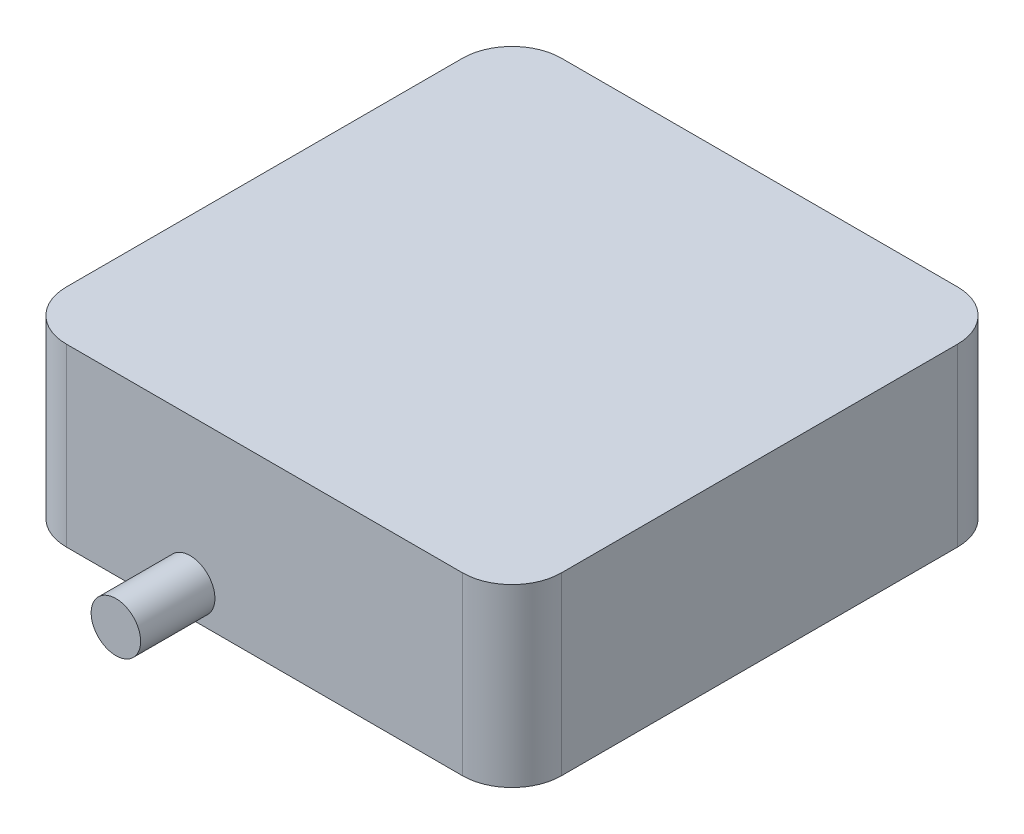
SolidWorks part; units mm, degrees
ref_plane "Front Plane" through (0, 0, 0) normal (0, 0, 1) x (1, 0, 0)
ref_plane "Top Plane" through (0, 0, 0) normal (0, 1, 0) x (1, 0, 0)
ref_plane "Right Plane" through (0, 0, 0) normal (1, 0, 0) x (0, 0, -1)
sketch "Sketch1" plane through (0, 0, 0) normal (0, 1, 0) x (1, 0, 0)
  line L1 (-100, -100) -> (100, -100)
  line L2 (-100, -100) -> (-100, 100)
  line L3 (-100, 100) -> (100, 100)
  line L4 (100, -100) -> (100, 100)
  line L5 (-100, -100) -> (100, 100) construction
  line L6 (-100, 100) -> (100, -100) construction
  point P0 (0, 0)
  dimension "D1" = 200
  dimension "D2" = 200
extrude "Boss-Extrude1" add sketch "Sketch1" along normal blind 71
fillet "Fillet1" radius 20 4 edges at (-100, 35.5, -100) (100, 35.5, -100) (100, 35.5, 100) (-100, 35.5, 100)
sketch "Sketch2" plane through (0, 0, 100) normal (0, 0, 1) x (1, 0, 0)
  line L0 (-30, 71) -> (-30, 0) construction
  line L1 (-80, 71) -> (80, 71) construction
  line L2 (-80, 0) -> (80, 0) construction
  line L3 (-100, 0) -> (-100, 71) construction
  line L4 (-100, 12) -> (100, 12) construction
  line L5 (100, 71) -> (100, 0) construction
  circle A0 centre (-30, 12) radius 10
  dimension "D2" = 20
  dimension "D1" = 70
  dimension "D3" = 12
extrude "Boss-Extrude2" add sketch "Sketch2" along normal blind 30
